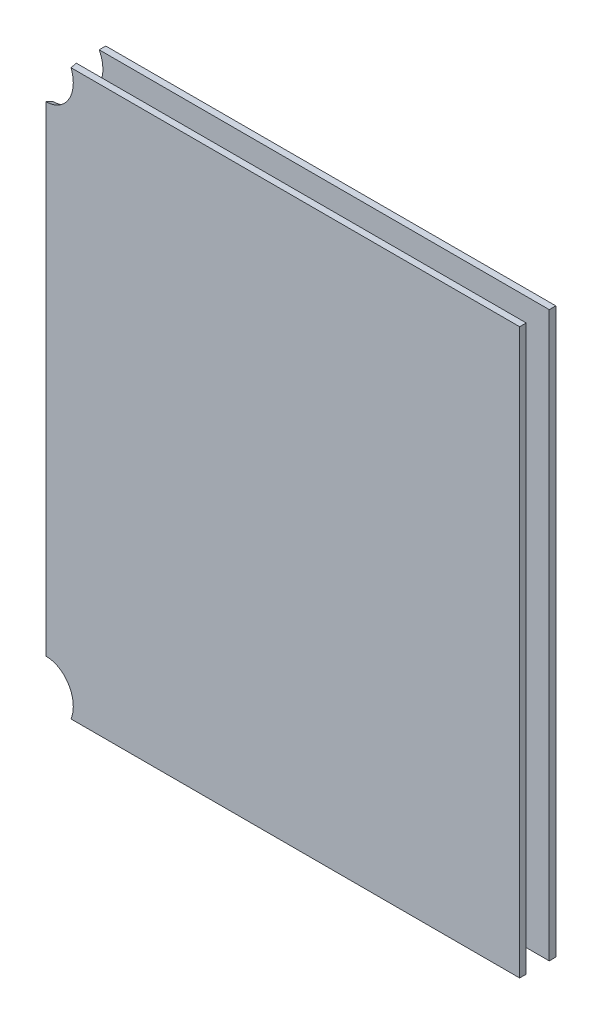
SolidWorks part; units mm, degrees
material "6061-T6 (SS)"
ref_plane "X-Y Datum" through (0, 0, 0) normal (0, 0, 1) x (1, 0, 0)
ref_plane "X-Z Datum" through (0, 0, 0) normal (0, 1, 0) x (1, 0, 0)
ref_plane "Y-Z Datum" through (0, 0, 0) normal (1, 0, 0) x (0, 0, -1)
ref_plane "Plane1" through (0, 0, 0) normal (0, 0, 1) x (1, 0, 0)
sketch "Sketch2" plane through (0, 0, 0) normal (0, 0, 1) x (1, 0, 0)
  line L4 (906.3228, -136.1666) -> (906.3228, 136.1666)
  line L5 (1134.9228, 136.1666) -> (906.3228, 136.1666)
  line L6 (1134.9228, -136.1666) -> (906.3228, -136.1666)
  line L7 (1134.9228, -136.1666) -> (1134.9228, 136.1666)
extrude "Boss-Extrude2" add sketch "Sketch2" along normal mid plane 3.175
ref_plane "Plane3" through (906.3228, 136.1666, 13.97) normal (0, -0.4228, -0.9062) x (-1, 0, 0)
sketch "Sketch4" plane through (906.3228, 136.1666, 13.97) normal (0, -0.4228, -0.9062) x (-1, 0, 0)
  circle A0 centre (0, 0) radius 13.081
  dimension "D1" = 26.162
extrude "Cut-Extrude2" cut sketch "Sketch4" along normal through all
mirror "Mirror2" about plane through (0, 0, 0) normal (0, 1, 0) of "Cut-Extrude2"
ref_plane "Plane4" through (0, 0, -12.7) normal (0, 0, 1) x (1, 0, 0)
sketch "Sketch5" plane through (0, 0, -12.7) normal (0, 0, 1) x (1, 0, 0)
  line L4 (906.3228, 114.4725) -> (906.3228, -114.4725)
  line L5 (1134.9228, 136.1666) -> (917.6294, 136.1666)
  line L6 (1134.9228, -136.1666) -> (1134.9228, 136.1666)
  line L7 (917.6294, -136.1666) -> (1134.9228, -136.1666)
  line L8 (906.3228, 114.4725) -> (906.3228, -114.4725)
  line L9 (1134.9228, 136.1666) -> (917.6294, 136.1666)
  line L10 (1134.9228, -136.1666) -> (1134.9228, 136.1666)
  line L11 (917.6294, -136.1666) -> (1134.9228, -136.1666)
  ellipse E2 centre (906.3228, -128.9075) end of major axis (906.3228, -143.3424) minor radius 13.081 (917.6294, -136.1666) -> (906.3228, -114.4725) ccw
  ellipse E3 centre (906.3228, 128.9075) end of major axis (906.3228, 143.3424) minor radius 13.081 (906.3228, 114.4725) -> (917.6294, 136.1666) ccw
  ellipse E4 centre (906.3228, -128.9075) end of major axis (906.3228, -143.3424) minor radius 13.081 (917.6294, -136.1666) -> (906.3228, -114.4725) ccw
  ellipse E5 centre (906.3228, 128.9075) end of major axis (906.3228, 143.3424) minor radius 13.081 (906.3228, 114.4725) -> (917.6294, 136.1666) ccw
  dimension "D1" = 0
extrude "Boss-Extrude3" add sketch "Sketch5" against normal blind 3.175 separate body
